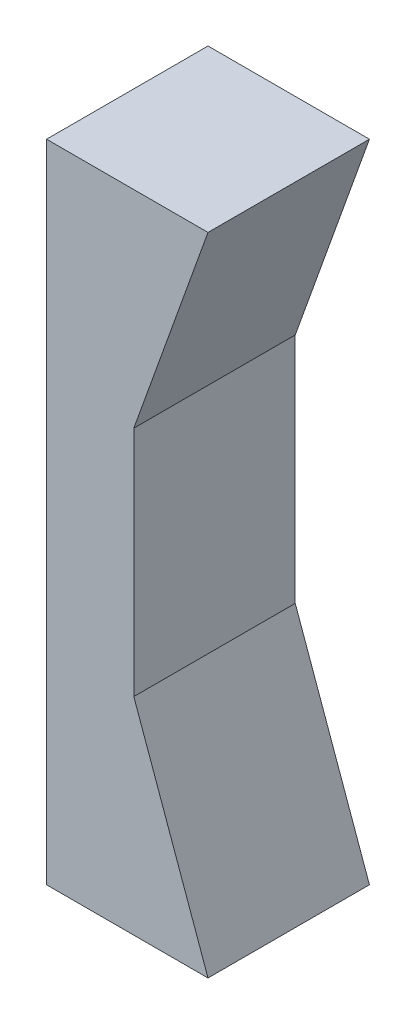
SolidWorks part; units mm, degrees
ref_plane "Front Plane" through (0, 0, 0) normal (1, 0, 0) x (0, 1, 0)
ref_plane "Top Plane" through (0, 0, 0) normal (0, 0, 1) x (0, 1, 0)
ref_plane "Right Plane" through (0, 0, 0) normal (0, 1, 0) x (-1, 0, 0)
sketch "Sketch1" plane through (0, 0, 0) normal (0, 0, 1) x (0, 1, 0)
  line L1 (-500, -125) -> (500, -125)
  line L2 (-500, -125) -> (-500, 125)
  line L3 (-500, 125) -> (500, 125)
  line L4 (500, -125) -> (500, 125)
  line L5 (-500, -125) -> (500, 125) construction
  line L6 (-500, 125) -> (500, -125) construction
  point P0 (0, 0)
  dimension "D1" = 1000
  dimension "D2" = 250
extrude "Boss-Extrude1" add sketch "Sketch1" along normal blind 250
sketch "Sketch2" plane through (0, 0, 250) normal (0, 0, 1) x (0, -1, 0)
  line L0 (-500, 125) -> (-180, 10.1087)
  line L1 (-180, 10.1087) -> (180, 10.1087)
  line L2 (180, 10.1087) -> (500, 125)
  line L3 (500, 125) -> (-500, 125)
  dimension "D1" = 360
  dimension "D2" = 340
extrude "Cut-Extrude1" cut sketch "Sketch2" against normal through all
shell "Shell1" thickness 1
